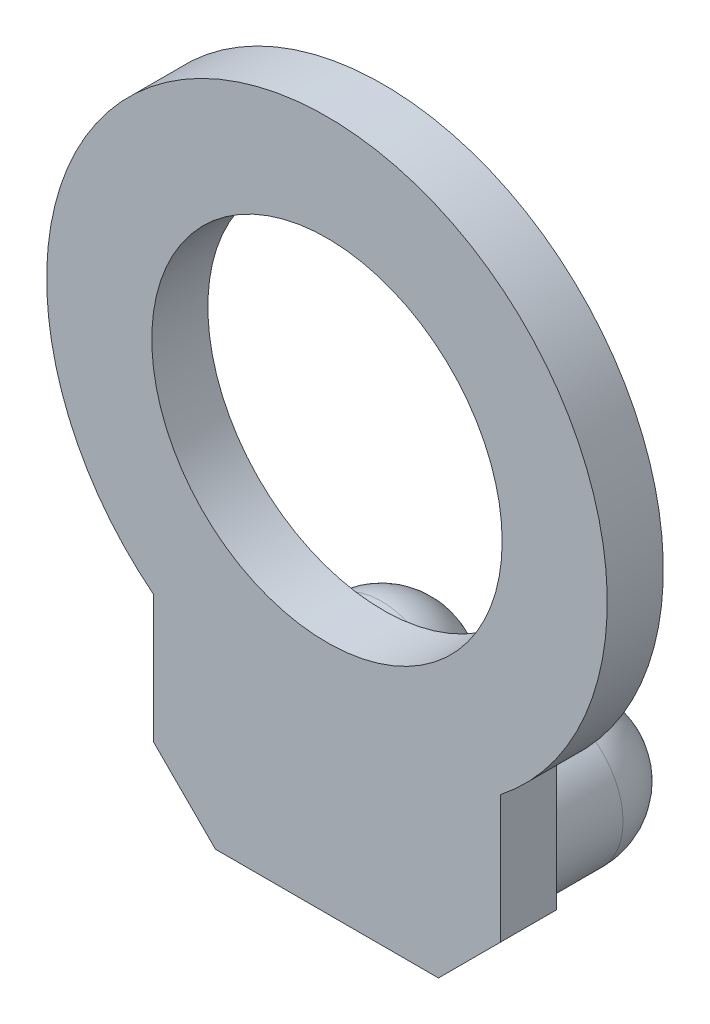
SolidWorks part; units mm, degrees
ref_plane "Front Plane" through (0, 0, 0) normal (0, 0, 1) x (1, 0, 0)
ref_plane "Top Plane" through (0, 0, 0) normal (0, 1, 0) x (1, 0, 0)
ref_plane "Right Plane" through (0, 0, 0) normal (1, 0, 0) x (0, 0, -1)
sketch "Sketch1" plane through (0, 0, 0) normal (0, 0, 1) x (1, 0, 0)
  line L0 (-4.95, -6.2847) -> (-4.95, -9.9322)
  line L1 (-3.1822, -11.7) -> (3.1822, -11.7)
  line L2 (4.95, -9.9322) -> (4.95, -6.2847)
  line L3 (-4.95, -9.9322) -> (-3.1822, -11.7)
  line L4 (4.95, -9.9322) -> (3.1822, -11.7)
  arc A0 (4.95, -6.2847) -> (-4.95, -6.2847) centre (0, 0) ccw
  circle A2 centre (-2.45, -9.2) radius 2
  circle A3 centre (2.45, -9.2) radius 2
  circle A4 centre (0, 0) radius 5
  dimension "D1" = 9.9
  dimension "D3" = 16
  dimension "D9" = 4
  dimension "D10" = 4
  dimension "D2" = 4.95
  dimension "D4" = 11.7
  dimension "D5" = 45
  dimension "D6" = 45
  dimension "D7" = 2.5
  dimension "D8" = 2.5
  dimension "D11" = 2.5
  dimension "D12" = 2.5
  dimension "D13" = 2.5
  dimension "D14" = 2.5
extrude "Boss-Extrude1" add sketch "Sketch1" along normal blind 1.6 contours L2 A0 L0 L3 L1 L4 A4 A3 A2
sketch "Sketch2" plane through (0, 0, 1.6) normal (0, 0, 1) x (1, 0, 0)
  circle A8 centre (2.45, -9.2) radius 2
  circle A9 centre (2.45, -9.2) radius 2
  circle A11 centre (-2.45, -9.2) radius 2
  circle A12 centre (-2.45, -9.2) radius 2
  dimension "D1" = 0
  dimension "D2" = 0
extrude "Boss-Extrude2" add sketch "Sketch2" against normal blind 6
fillet "Fillet1" radius 2 2 edges at (-0.45, -9.2, -4.4) (4.45, -9.2, -4.4)
sketch "Sketch3" plane through (0, 0, 1.6) normal (0, 0, 1) x (1, 0, 0)
  circle A0 centre (0, 0) radius 6.5 construction
  circle A1 centre (-6.5, 0) radius 1
  circle A2 centre (-6.0052, 2.4874) radius 1
  circle A3 centre (-4.5962, 4.5962) radius 1
  circle A4 centre (-2.4874, 6.0052) radius 1
  circle A5 centre (0, 6.5) radius 1
  circle A6 centre (2.4874, 6.0052) radius 1
  circle A7 centre (4.5962, 4.5962) radius 1
  circle A8 centre (6.0052, 2.4874) radius 1
  circle A9 centre (6.5, 0) radius 1
  circle A10 centre (6.0052, -2.4874) radius 1
  circle A11 centre (4.5962, -4.5962) radius 1
  circle A12 centre (2.4874, -6.0052) radius 1
  circle A13 centre (0, -6.5) radius 1
  circle A14 centre (-2.4874, -6.0052) radius 1
  circle A15 centre (-4.5962, -4.5962) radius 1
  circle A16 centre (-6.0052, -2.4874) radius 1
  point P37 (0, 0)
  dimension "D1" = 16
